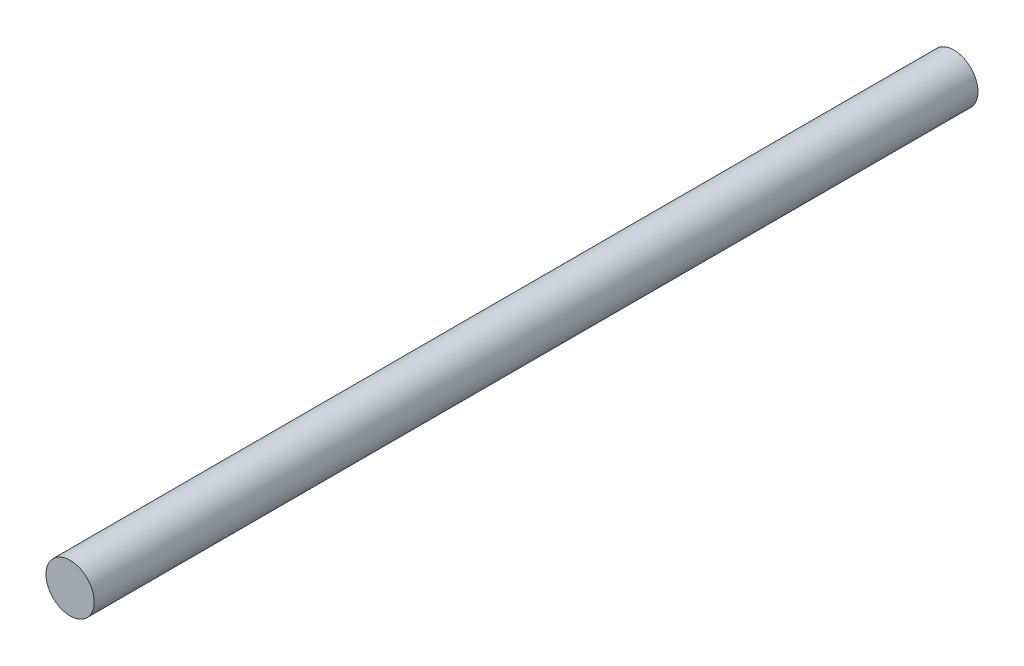
SolidWorks part; units mm, degrees
ref_plane "前视基准面" through (0, 0, 0) normal (0, 0, 1) x (1, 0, 0)
ref_plane "上视基准面" through (0, 0, 0) normal (0, 1, 0) x (1, 0, 0)
ref_plane "右视基准面" through (0, 0, 0) normal (1, 0, 0) x (0, 0, -1)
sketch "Sketch1" plane through (0, 0, 0) normal (0, 0, 1) x (1, 0, 0)
  circle A0 centre (0, 0) radius 8
extrude "Boss-Extrude1" add sketch "Sketch1" along normal blind 293
